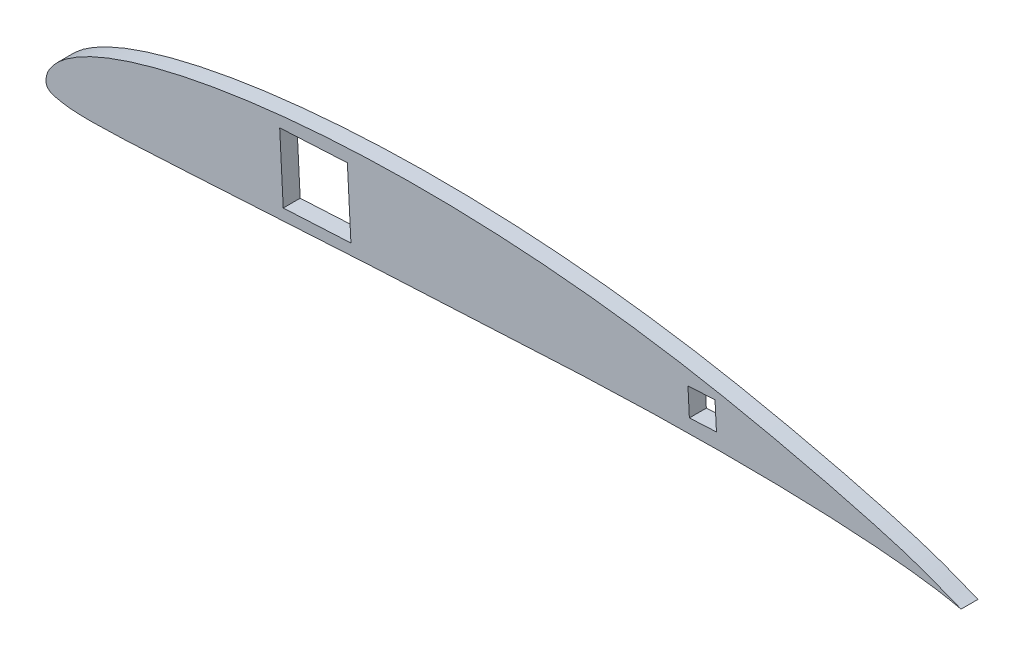
SolidWorks part; units mm, degrees
ref_plane "Front Plane" through (0, 0, 0) normal (0, 0, 1) x (1, 0, 0)
ref_plane "Top Plane" through (0, 0, 0) normal (0, 1, 0) x (1, 0, 0)
ref_plane "Right Plane" through (0, 0, 0) normal (1, 0, 0) x (0, 0, -1)
curve "Curve1"
  spline degree 3 poles (0.9958, 0.001, 0) (1.001, -0.0003, 0) (0.996, 0.0013, 0) (0.9922, 0.003, 0) (0.9833, 0.0065, 0) (0.9728, 0.0108, 0) (0.9593, 0.0159, 0) (0.9435, 0.0213, 0) (0.9252, 0.0268, 0) (0.9044, 0.0327, 0) (0.8814, 0.0389, 0) (0.8563, 0.0453, 0) (0.8293, 0.0518, 0) (0.8006, 0.0584, 0) (0.7704, 0.0649, 0) (0.7389, 0.0713, 0) (0.7064, 0.0773, 0) (0.673, 0.0828, 0) (0.6387, 0.0877, 0) (0.6038, 0.092, 0) (0.5685, 0.0956, 0) (0.5327, 0.0985, 0) (0.4969, 0.1007, 0) (0.461, 0.1021, 0) (0.4254, 0.1028, 0) (0.3902, 0.1027, 0) (0.3555, 0.1019, 0) (0.3216, 0.1003, 0) (0.2886, 0.098, 0) (0.2567, 0.0951, 0) (0.2261, 0.0915, 0) (0.1969, 0.0872, 0) (0.1693, 0.0824, 0) (0.1435, 0.0771, 0) (0.1194, 0.0713, 0) (0.0974, 0.0651, 0) (0.0775, 0.0585, 0) (0.0597, 0.0516, 0) (0.0442, 0.0445, 0) (0.0311, 0.0371, 0) (0.0202, 0.0297, 0) (0.0116, 0.0223, 0) (0.0054, 0.015, 0) (0.0013, 0.0079, 0) (-0.0002, 0.0014, 0) (-0.0001, -0.0048, 0) (0.0043, -0.0095, 0) (0.0118, -0.0115, 0) (0.0218, -0.0136, 0) (0.0351, -0.0145, 0) (0.0516, -0.0147, 0) (0.0712, -0.0142, 0) (0.0939, -0.0133, 0) (0.1196, -0.0119, 0) (0.148, -0.0103, 0) (0.1789, -0.0084, 0) (0.2122, -0.0064, 0) (0.2475, -0.0043, 0) (0.2847, -0.0021, 0) (0.3234, 0.0002, 0) (0.3633, 0.0024, 0) (0.4042, 0.0045, 0) (0.4459, 0.0067, 0) (0.4879, 0.0089, 0) (0.5303, 0.0112, 0) (0.5728, 0.0133, 0) (0.615, 0.0151, 0) (0.6567, 0.0164, 0) (0.6974, 0.0173, 0) (0.7368, 0.0177, 0) (0.7745, 0.0176, 0) (0.8103, 0.017, 0) (0.8438, 0.016, 0) (0.8747, 0.0146, 0) (0.9027, 0.0128, 0) (0.9276, 0.0107, 0) (0.949, 0.0085, 0) (0.967, 0.0061, 0) (0.9805, 0.004, 0) (0.9914, 0.0018, 0) (0.9958, 0.001, 0) (1.001, -0.0003, 0) (0.996, 0.0013, 0) knots -0.008893 -0.003951 -0.000989 0 0.000979 0.003786 0.008179 0.01394 0.020915 0.029057 0.038414 0.048974 0.060645 0.073334 0.086939 0.101355 0.116471 0.132171 0.148332 0.16489 0.181807 0.198987 0.216369 0.233891 0.251455 0.26899 0.28641 0.303633 0.320589 0.337187 0.353353 0.369012 0.384083 0.3985 0.412191 0.425098 0.437171 0.448351 0.458606 0.467901 0.476216 0.483573 0.48997 0.495456 0.500132 0.503992 0.50723 0.509987 0.512501 0.516074 0.521095 0.527571 0.535587 0.545177 0.556302 0.568875 0.5828 0.597975 0.614286 0.631613 0.649826 0.668792 0.688371 0.708417 0.728797 0.749399 0.770146 0.790953 0.811664 0.832074 0.851999 0.871282 0.889761 0.90728 0.923686 0.938833 0.952579 0.964796 0.975365 0.984179 0.991107 0.996049 0.999011 1 1.000979 1.003786 1.008179 periodic
sketch "Sketch1" plane through (0, 0, 0) normal (0, 0, 1) x (1, 0, 0)
  line L0 (270, 0) -> (0, 0) construction
  line L1 (0, 64.6542) -> (0, 76.1166) construction
  line L2 (68.9533, 22.4726) -> (70, 2.5)
  line L3 (70, 2.5) -> (89.9726, 3.5467)
  line L4 (89.9726, 3.5467) -> (88.9259, 23.5193)
  line L5 (88.9259, 23.5193) -> (68.9533, 22.4726)
  line L7 (189.4169, 16.7694) -> (189.8355, 8.7803)
  line L8 (189.8355, 8.7803) -> (197.8246, 9.199)
  line L9 (197.8246, 9.199) -> (197.4059, 17.188)
  line L10 (197.4059, 17.188) -> (189.4169, 16.7694)
  spline S1 degree 3 poles (268.8608, 0.2788) (270.2805, -0.0806) (268.9329, 0.3525) (267.9068, 0.8001) (265.4933, 1.7547) (262.6484, 2.9195) (259.0225, 4.2994) (254.7614, 5.7542) (249.8101, 7.2653) (244.2102, 8.86) (237.9937, 10.5351) (231.2122, 12.2665) (223.9187, 14.036) (216.1682, 15.8177) (208.0193, 17.5868) (199.5316, 19.3088) (190.7576, 20.9527) (181.7291, 22.4466) (172.4857, 23.7789) (163.0672, 24.9496) (153.5144, 25.926) (143.8738, 26.7206) (134.1907, 27.3179) (124.5158, 27.7065) (114.898, 27.9027) (105.3849, 27.8869) (96.0259, 27.668) (86.8684, 27.2538) (77.9613, 26.6449) (69.3513, 25.8546) (61.0839, 24.8872) (53.2043, 23.7511) (45.7522, 22.4644) (38.7673, 21.0309) (32.2855, 19.4683) (26.3378, 17.7935) (20.9568, 16.0158) (16.1613, 14.1676) (11.9757, 12.2431) (8.4191, 10.259) (5.4722, 8.2745) (3.1624, 6.2613) (1.479, 4.2931) (0.3711, 2.3888) (-0.0282, 0.6149) (-0.0142, -1.0346) (1.1702, -2.329) (3.1916, -2.8616) (5.9009, -3.4146) (9.5038, -3.671) (13.9401, -3.7323) (19.2374, -3.6152) (25.3684, -3.3609) (32.2954, -3.0045) (39.9657, -2.5702) (48.3225, -2.0715) (57.305, -1.5317) (66.8468, -0.9614) (76.8781, -0.3783) (87.3251, 0.2099) (98.1107, 0.7936) (109.1579, 1.3676) (120.3938, 1.9439) (131.7579, 2.5421) (143.2011, 3.1378) (154.6659, 3.7041) (166.073, 4.1742) (177.322, 4.5164) (188.3105, 4.7407) (198.945, 4.8392) (209.1363, 4.8086) (218.7963, 4.6499) (227.8386, 4.3681) (236.1813, 3.9747) (243.7431, 3.4847) (250.4593, 2.9183) (256.239, 2.3104) (261.0889, 1.668) (264.7489, 1.0836) (267.6685, 0.4898) (268.8608, 0.2788) (270.2805, -0.0806) (268.9329, 0.3525) knots -0.008893 -0.003951 -0.000989 0 0.000979 0.003786 0.008179 0.01394 0.020915 0.029057 0.038414 0.048974 0.060645 0.073334 0.086939 0.101355 0.116471 0.132171 0.148332 0.16489 0.181807 0.198987 0.216369 0.233891 0.251455 0.26899 0.28641 0.303633 0.320589 0.337187 0.353353 0.369012 0.384083 0.3985 0.412191 0.425098 0.437171 0.448351 0.458606 0.467901 0.476216 0.483573 0.48997 0.495456 0.500132 0.503992 0.50723 0.509987 0.512501 0.516074 0.521095 0.527571 0.535587 0.545177 0.556302 0.568875 0.5828 0.597975 0.614286 0.631613 0.649826 0.668792 0.688371 0.708417 0.728797 0.749399 0.770146 0.790953 0.811664 0.832074 0.851999 0.871282 0.889761 0.90728 0.923686 0.938833 0.952579 0.964796 0.975365 0.984179 0.991107 0.996049 0.999011 1 1.000979 1.003786 1.008179 only from (270, 0) to (270, 0)
  dimension "D1" = 270
  dimension "D2" = 20
  dimension "D3" = 8
  dimension "D4" = 100
  dimension "D5" = 2.5
  dimension "D6" = 70
  dimension "D7" = 3
extrude "Boss-Extrude1" add sketch "Sketch1" along normal blind 5 contours S1
equation "\"AoA\"=5"
